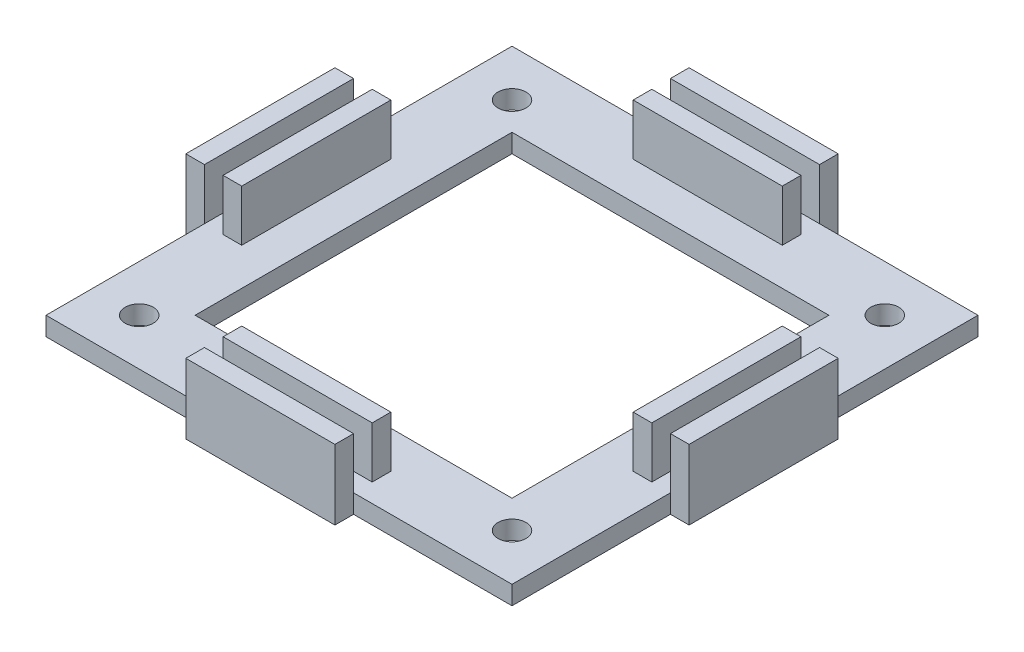
SolidWorks part; units mm, degrees
ref_plane "Front Plane" through (0, 0, 0) normal (0, 0, 1) x (1, 0, 0)
ref_plane "Top Plane" through (0, 0, 0) normal (0, 1, 0) x (1, 0, 0)
ref_plane "Right Plane" through (0, 0, 0) normal (1, 0, 0) x (0, 0, -1)
sketch "Sketch1" plane through (0, 0, 0) normal (0, 1, 0) x (1, 0, 0)
  line L1 (-25, -25) -> (25, -25)
  line L2 (-25, -25) -> (-25, 25)
  line L3 (-25, 25) -> (25, 25)
  line L4 (25, -25) -> (25, 25)
  line L5 (-25, -25) -> (25, 25) construction
  line L6 (-25, 25) -> (25, -25) construction
  line L7 (-17, -17) -> (17, -17)
  line L8 (-17, -17) -> (-17, 17)
  line L9 (-17, 17) -> (17, 17)
  line L10 (17, -17) -> (17, 17)
  line L11 (-17, -17) -> (17, 17) construction
  line L12 (-17, 17) -> (17, -17) construction
  point P0 (0, 0)
  point P6 (0, 0)
  dimension "D1" = 50
  dimension "D2" = 8
extrude "Boss-Extrude1" add sketch "Sketch1" along normal blind 2
sketch "Sketch2" plane through (0, 2, 0) normal (0, 1, 0) x (1, 0, 0)
  line L1 (-20, -20) -> (20, -20) construction
  line L2 (-20, -20) -> (-20, 20) construction
  line L3 (-20, 20) -> (20, 20) construction
  line L4 (20, -20) -> (20, 20) construction
  line L5 (-20, -20) -> (20, 20) construction
  line L6 (-20, 20) -> (20, -20) construction
  circle A0 centre (-20, 20) radius 1.5
  circle A1 centre (20, 20) radius 1.5
  circle A2 centre (20, -20) radius 1.5
  circle A3 centre (-20, -20) radius 1.5
  point P0 (0, 0)
  dimension "D2" = 3
  dimension "D1" = 40
extrude "Cut-Extrude1" cut sketch "Sketch2" against normal up to surface (2 mm away) up to face at (0, 0, 0)
sketch "Sketch7" plane through (0, 0, 0) normal (0, 1, 0) x (1, 0, 0)
  line L0 (8, 23) -> (-8, 23)
  line L5 (-25, 25) -> (-25, -25) construction
  line L6 (-25, 8) -> (-27, 8)
  line L7 (-25, 8) -> (-25, -8)
  line L8 (-25, -8) -> (-27, -8)
  line L9 (-27, 8) -> (-27, -8)
  line L10 (8, 23) -> (8, 21)
  line L11 (-23, 8) -> (-21, 8)
  line L12 (-23, 8) -> (-23, -8)
  line L13 (-23, -8) -> (-21, -8)
  line L14 (-21, 8) -> (-21, -8)
  line L15 (8, 21) -> (-8, 21)
  line L16 (-8, 23) -> (-8, 21)
  line L17 (8, 25) -> (-8, 25)
  line L18 (8, 25) -> (8, 27)
  line L19 (8, 27) -> (-8, 27)
  line L20 (-8, 25) -> (-8, 27)
  line L21 (23, -8) -> (23, 8)
  line L22 (23, -8) -> (21, -8)
  line L23 (21, -8) -> (21, 8)
  line L24 (23, 8) -> (21, 8)
  line L25 (25, -8) -> (25, 8)
  line L26 (25, -8) -> (27, -8)
  line L27 (27, -8) -> (27, 8)
  line L28 (25, 8) -> (27, 8)
  line L29 (-8, -23) -> (8, -23)
  line L30 (-8, -23) -> (-8, -21)
  line L31 (-8, -21) -> (8, -21)
  line L32 (8, -23) -> (8, -21)
  line L33 (-8, -25) -> (8, -25)
  line L34 (-8, -25) -> (-8, -27)
  line L35 (-8, -27) -> (8, -27)
  line L36 (8, -25) -> (8, -27)
  point P10 (-25, 0)
  point P11 (-23, 0)
  point P13 (0, 0)
  point P40 (0, 0)
  dimension "D1" = 2
  dimension "D2" = 2
  dimension "D3" = 2
  dimension "D4" = 16
  dimension "D5" = 4
extrude "Boss-Extrude4" add sketch "Sketch7" along normal blind 7.5
